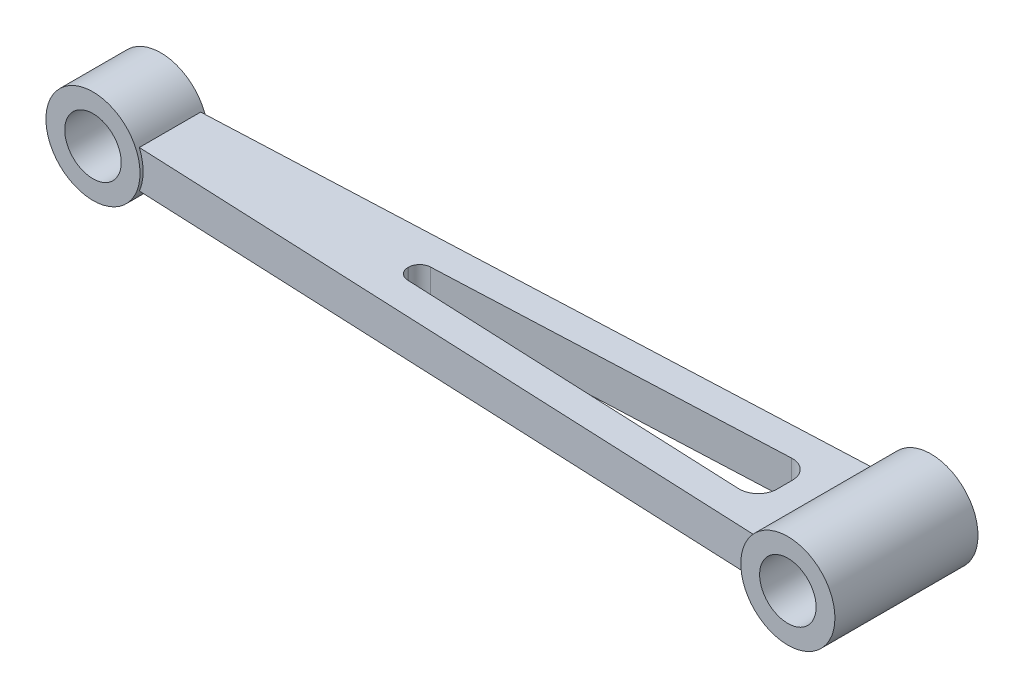
SolidWorks part; units mm, degrees
material "7075-T6 (SN)"
ref_plane "Front Plane" through (0, 0, 0) normal (0, 0, 1) x (1, 0, 0)
ref_plane "Top Plane" through (0, 0, 0) normal (0, 1, 0) x (1, 0, 0)
ref_plane "Right Plane" through (0, 0, 0) normal (1, 0, 0) x (0, 0, -1)
sketch "Sketch1" plane through (0, 0, 0) normal (0, 0, 1) x (1, 0, 0)
  line L0 (0, 0) -> (-97.28, 0) construction
  circle A0 centre (-97.28, 0) radius 12.5
  dimension "D2" = 25
  dimension "D1" = 97.28
extrude "Boss-Extrude1" add sketch "Sketch1" along normal mid plane 18
sketch "Sketch2" plane through (0, 0, 0) normal (0, 0, 1) x (1, 0, 0)
  line L0 (0, 0) -> (97.28, 0) construction
  circle A0 centre (97.28, 0) radius 12.5
  dimension "D2" = 25
  dimension "D1" = 97.28
extrude "Boss-Extrude2" add sketch "Sketch2" along normal mid plane 38 separate body
sketch "Sketch3" plane through (0, 0, 0) normal (0, 1, 0) x (1, 0, 0)
  line L0 (-97.28, 7.6452) -> (-97.28, 0) construction
  line L2 (-97.28, 0) -> (97.28, 0) construction
  line L3 (-97.28, 7.6452) -> (97.28, 16.1399)
  line L4 (-97.28, -7.6452) -> (97.28, -16.1399)
  line L5 (-97.28, 7.6452) -> (-97.28, -7.6452)
  line L6 (97.28, 16.1399) -> (97.28, -16.1399)
  dimension "D1" = 5
extrude "Boss-Extrude3" add sketch "Sketch3" along normal mid plane 10
sketch "Sketch4" plane through (0, 5, 0) normal (0, 1, 0) x (1, 0, 0)
  line L2 (86.1725, 7.6473) -> (-85.4746, 0.153)
  line L3 (72.2239, 7.0383) -> (-19.6888, 3.0253)
  line L4 (77.442, 2.043) -> (77.442, -2.043)
  line L5 (-85.4746, -0.153) -> (86.1725, -7.6473)
  line L6 (-19.6888, -3.0253) -> (72.2239, -7.0383)
  line L9 (-22.558, 0.0281) -> (-22.558, -0.0281)
  line L10 (-22.558, 32.5397) -> (-22.558, -28.8369) construction
  line L11 (77.442, 32.5397) -> (77.442, -28.8369) construction
  arc A0 (-22.558, 0.0281) -> (-19.6888, 3.0253) centre (-19.558, 0.0281) cw
  arc A1 (-19.6888, -3.0253) -> (-22.558, -0.0281) centre (-19.558, -0.0281) cw
  arc A2 (72.2239, 7.0383) -> (77.442, 2.043) centre (72.442, 2.043) cw
  arc A3 (77.442, -2.043) -> (72.2239, -7.0383) centre (72.442, -2.043) cw
  point P9 (-22.558, 2.9)
  point P17 (-22.558, -2.9)
  dimension "D5" = 3
  dimension "D6" = 5
  dimension "D3" = 5.8
  dimension "D1" = 8
  dimension "D2" = 8
  dimension "D4" = 100
extrude "Cut-Extrude1" cut sketch "Sketch4" against normal mid plane 53
sketch "Sketch5" plane through (0, 0, 0) normal (0, 0, 1) x (1, 0, 0)
  circle A0 centre (-97.28, 0) radius 7.5
  circle A1 centre (97.28, 0) radius 7.5
  dimension "D1" = 15
  dimension "D2" = 15
extrude "Cut-Extrude2" cut sketch "Sketch5" against normal mid plane 53
